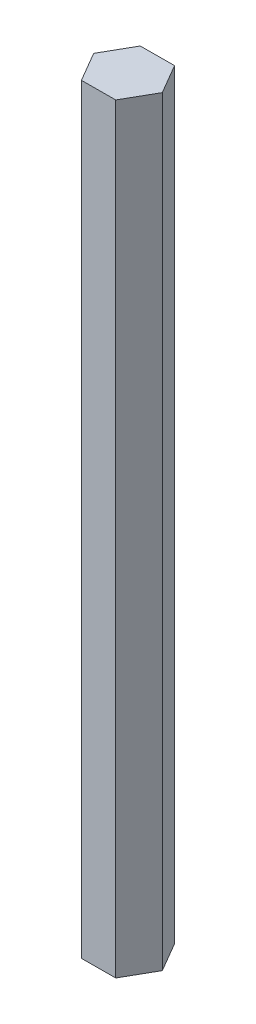
SolidWorks part; units mm, degrees
ref_plane "Alzado" through (0, 0, 0) normal (0, 0, 1) x (1, 0, 0)
ref_plane "Planta" through (0, 0, 0) normal (0, 1, 0) x (1, 0, 0)
ref_plane "Vista lateral" through (0, 0, 0) normal (1, 0, 0) x (0, 0, -1)
sketch "Croquis1" plane through (0, 0, 0) normal (0, 1, 0) x (1, 0, 0)
  line L1 (-3.6325, -6.3693) -> (3.6997, -6.3305)
  line L2 (3.6997, -6.3305) -> (7.3322, 0.0388)
  line L3 (7.3322, 0.0388) -> (3.6325, 6.3693)
  line L4 (3.6325, 6.3693) -> (-3.6997, 6.3305)
  line L5 (-3.6997, 6.3305) -> (-7.3322, -0.0388)
  line L6 (-7.3322, -0.0388) -> (-3.6325, -6.3693)
  circle A0 centre (0, 0) radius 6.35 construction
  dimension "D1" = 12.7
extrude "Saliente-Extruir1" add sketch "Croquis1" along normal blind 116
sketch "Croquis2" plane through (0, 116, 0) normal (0, 1, 0) x (1, 0, 0)
  line L1 (7.3322, 0.0388) -> (3.6325, 6.3693)
  line L2 (3.6325, 6.3693) -> (-3.6997, 6.3305)
  line L3 (-3.6997, 6.3305) -> (-7.3322, -0.0388)
  line L4 (-7.3322, -0.0388) -> (-3.6325, -6.3693)
  line L5 (-3.6325, -6.3693) -> (3.6997, -6.3305)
  line L6 (3.6997, -6.3305) -> (7.3322, 0.0388)
  circle A0 centre (0, 0) radius 6.35 construction
  point P0 (0, 0)
sketch "Croquis3" plane through (0, 0, 0) normal (0, -1, 0) x (1, 0, 0)
  point P0 (0, 0)
sketch "Croquis5" plane through (0, 116, 0) normal (0, 1, 0) x (1, 0, 0)
  line L1 (7.3322, 0.0388) -> (3.6325, 6.3693)
  line L2 (3.6325, 6.3693) -> (-3.6997, 6.3305)
  line L3 (-3.6997, 6.3305) -> (-7.3322, -0.0388)
  line L4 (-7.3322, -0.0388) -> (-3.6325, -6.3693)
  line L5 (-3.6325, -6.3693) -> (3.6997, -6.3305)
  line L6 (3.6997, -6.3305) -> (7.3322, 0.0388)
  circle A0 centre (0, 0) radius 6.35 construction
sketch "Croquis6" plane through (0, 0, 0) normal (0, -1, 0) x (1, 0, 0)
  line L1 (7.3322, -0.0388) -> (3.6997, 6.3305)
  line L2 (3.6997, 6.3305) -> (-3.6325, 6.3693)
  line L3 (-3.6325, 6.3693) -> (-7.3322, 0.0388)
  line L4 (-7.3322, 0.0388) -> (-3.6997, -6.3305)
  line L5 (-3.6997, -6.3305) -> (3.6325, -6.3693)
  line L6 (3.6325, -6.3693) -> (7.3322, -0.0388)
  circle A0 centre (0, 0) radius 6.35 construction
extrude "Saliente-Extruir3" add sketch "Croquis6" along normal blind 47.28
